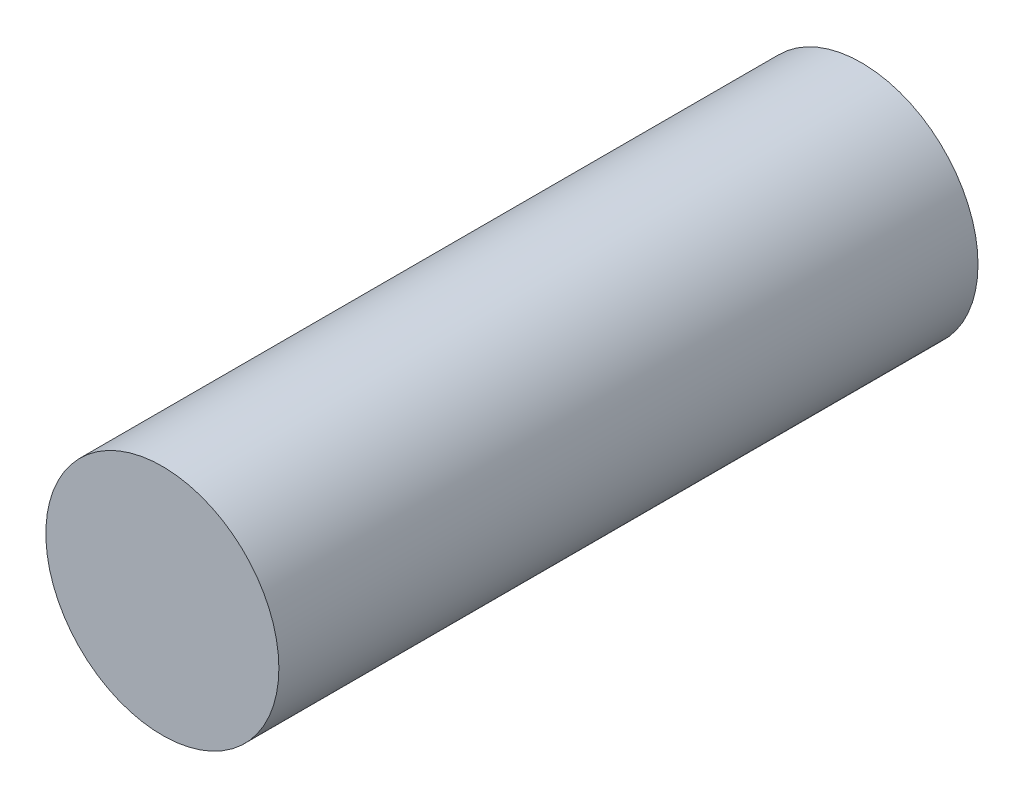
SolidWorks part; units mm, degrees
ref_plane "Plano frontal" through (0, 0, 0) normal (0, 0, 1) x (1, 0, 0)
ref_plane "Plano superior" through (0, 0, 0) normal (0, 1, 0) x (1, 0, 0)
ref_plane "Plano direito" through (0, 0, 0) normal (1, 0, 0) x (0, 0, -1)
sketch "Esboço1" plane through (0, 0, 0) normal (0, 0, 1) x (1, 0, 0)
  circle A0 centre (0, 0) radius 3
  dimension "D1" = 6
extrude "Ressalto-extrusão1" add sketch "Esboço1" along normal blind 18
